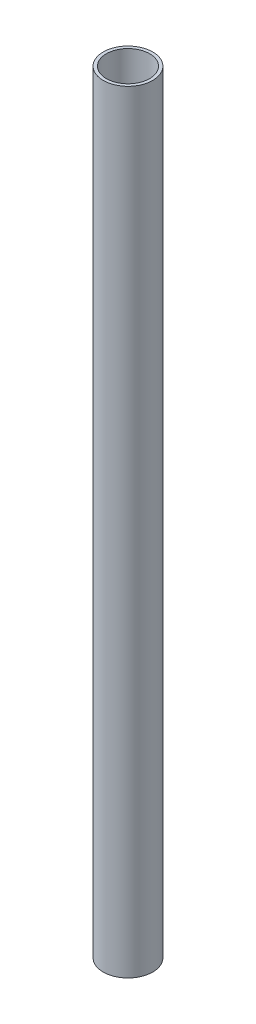
SolidWorks part; units mm, degrees
material "windcatcher"
ref_plane "Front Plane" through (0, 0, 0) normal (0, 0, 1) x (1, 0, 0)
ref_plane "Top Plane" through (0, 0, 0) normal (0, 1, 0) x (1, 0, 0)
ref_plane "Right Plane" through (0, 0, 0) normal (1, 0, 0) x (0, 0, -1)
sketch "Sketch1" plane through (0, 0, 0) normal (0, 1, 0) x (1, 0, 0)
  circle A0 centre (0, 0) radius 7
  circle A1 centre (0, 0) radius 8
  dimension "D1" = 16
  dimension "D2" = 14
extrude "Boss-Extrude1" add sketch "Sketch1" along normal blind 250
